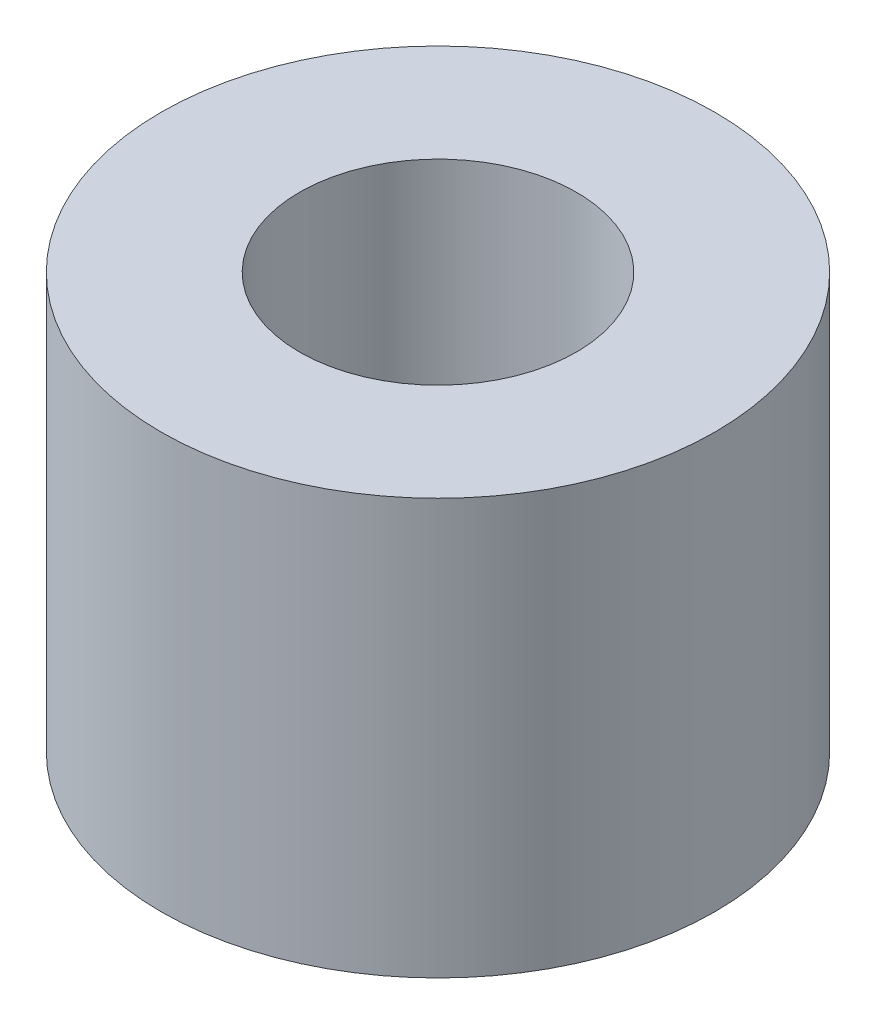
SolidWorks part; units mm, degrees
ref_plane "Front Plane" through (0, 0, 0) normal (0, 0, 1) x (1, 0, 0)
ref_plane "Top Plane" through (0, 0, 0) normal (0, 1, 0) x (1, 0, 0)
ref_plane "Right Plane" through (0, 0, 0) normal (1, 0, 0) x (0, 0, -1)
sketch "Sketch1" plane through (0, 0, 0) normal (0, 1, 0) x (1, 0, 0)
  circle A0 centre (0, 0) radius 4
  circle A1 centre (0, 0) radius 2
  dimension "D1" = 4
  dimension "D2" = 2
extrude "Boss-Extrude1" add sketch "Sketch1" along normal blind 5 contours A1
sketch "Sketch3" plane through (0, 0, 0) normal (0, -1, 0) x (1, 0, 0)
  circle A0 centre (0, 0) radius 4 construction
  circle A1 centre (0, 0) radius 4
extrude "Boss-Extrude2" add sketch "Sketch3" along normal blind 1
